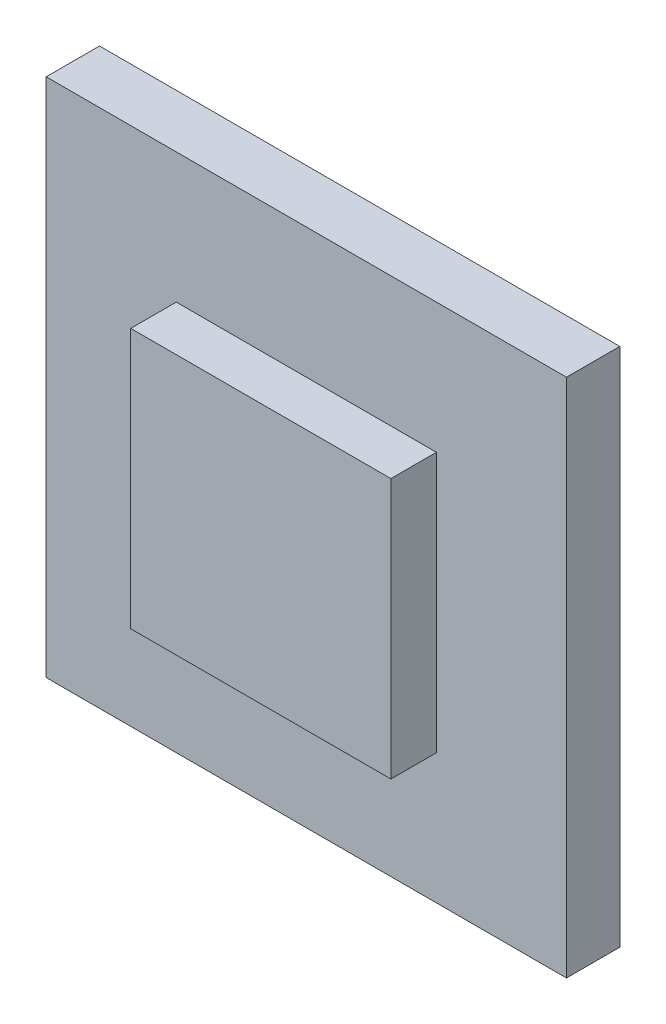
SolidWorks part; units mm, degrees
ref_plane "前视基准面" through (0, 0, 0) normal (0, 0, 1) x (1, 0, 0)
ref_plane "上视基准面" through (0, 0, 0) normal (0, 1, 0) x (1, 0, 0)
ref_plane "右视基准面" through (0, 0, 0) normal (1, 0, 0) x (0, 0, -1)
sketch "草图1" plane through (0, 0, 0) normal (0, 0, 1) x (1, 0, 0)
  line L1 (2, -2) -> (-2, -2)
  line L2 (2, -2) -> (2, 2)
  line L3 (2, 2) -> (-2, 2)
  line L4 (-2, -2) -> (-2, 2)
  line L5 (2, -2) -> (-2, 2) construction
  line L6 (2, 2) -> (-2, -2) construction
  point P0 (0, 0)
  dimension "D1" = 4
  dimension ".55" = 4
extrude "凸台-拉伸1" add sketch "草图1" along normal blind 0.41
sketch "草图2" plane through (0, 0, 0.41) normal (0, 0, 1) x (1, 0, 0)
  line L1 (1, -1) -> (-1, -1)
  line L2 (1, -1) -> (1, 1)
  line L3 (1, 1) -> (-1, 1)
  line L4 (-1, -1) -> (-1, 1)
  line L5 (1, -1) -> (-1, 1) construction
  line L6 (1, 1) -> (-1, -1) construction
  point P0 (0, 0)
  dimension "D1" = 2
  dimension "D2" = 2
extrude "凸台-拉伸2" add sketch "草图2" along normal blind 0.35
sketch "草图5" plane through (0, 0, 0) normal (0, 0, -1) x (-1, 0, 0)
  point P0 (0, 0)
sketch "草图6" plane through (0, 0, 0.76) normal (0, 0, 1) x (1, 0, 0)
  point P0 (0, 0)
sketch "草图7" plane through (0, 0, 0) normal (0, 0, -1) x (-1, 0, 0)
  line L0 (0, 2) -> (0, -2) construction
  line L1 (-2, 2) -> (2, 2) construction
  line L2 (2, -2) -> (-2, -2) construction
  line L3 (-2, 0) -> (2, 0) construction
  line L4 (-2, -2) -> (-2, 2) construction
  line L5 (2, 2) -> (2, -2) construction
  point P12 (0, 0)
sketch "草图8" plane through (0, 0, 0.76) normal (0, 0, 1) x (1, 0, 0)
  point P0 (0, 0)
sketch "草图9" plane through (0, 0, 0) normal (0, 0, -1) x (-1, 0, 0)
  line L1 (2, -2) -> (-2, -2) construction
  line L2 (2, -2) -> (2, 2) construction
  line L3 (2, 2) -> (-2, 2) construction
  line L4 (-2, -2) -> (-2, 2) construction
  line L5 (2, -2) -> (-2, 2) construction
  line L6 (2, 2) -> (-2, -2) construction
  point P0 (0, 0)
sketch "草图10" plane through (0, 0, 0.76) normal (0, 0, 1) x (1, 0, 0)
  line L0 (0, 1) -> (0, -1) construction
  line L1 (1, 1) -> (-1, 1) construction
  line L2 (-1, -1) -> (1, -1) construction
  line L3 (-1, 0) -> (1, 0) construction
  line L4 (-1, 1) -> (-1, -1) construction
  line L5 (1, -1) -> (1, 1) construction
  point P12 (0, 0)
